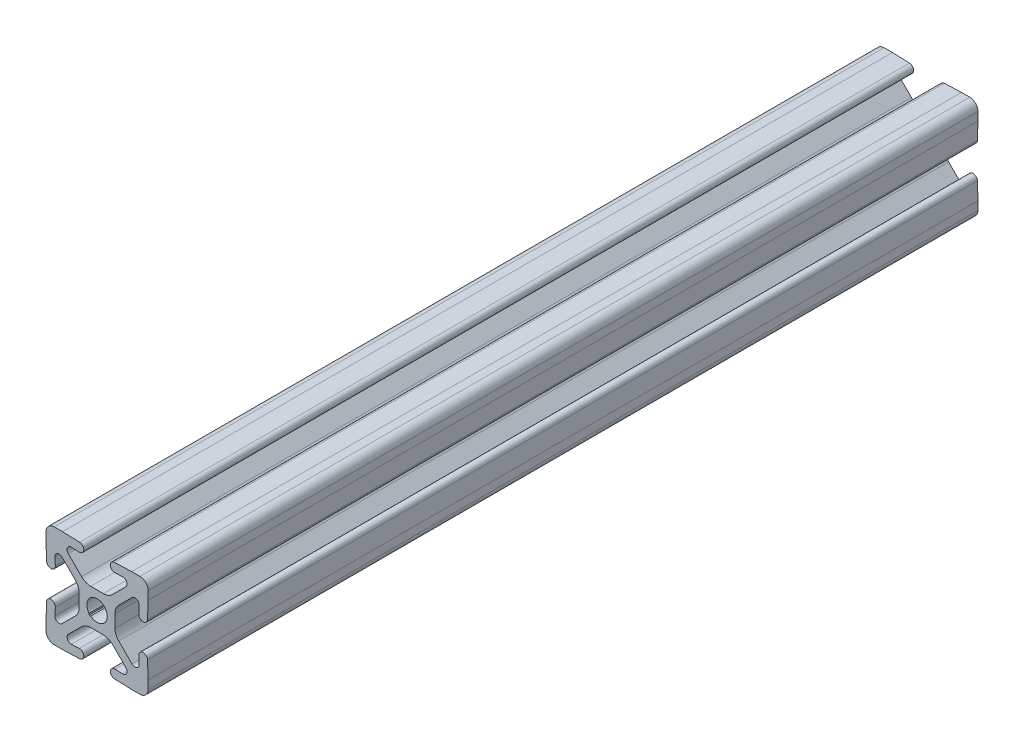
SolidWorks part; units mm, degrees
ref_plane "Front Plane" through (0, 0, 0) normal (0, 0, 1) x (1, 0, 0)
ref_plane "Top Plane" through (0, 0, 0) normal (0, 1, 0) x (1, 0, 0)
ref_plane "Right Plane" through (0, 0, 0) normal (1, 0, 0) x (0, 0, -1)
sketch "Model" plane through (0, 0, 0) normal (0, 0, 1) x (1, 0, 0)
  line L38 (50.6495, 75.4336) -> (50.2699, 75.4336)
  line L39 (50.2699, 75.4336) -> (50.2699, 75.8133)
  line L40 (50.66, 72.9999) -> (53.7746, 72.9999)
  line L41 (56.0196, 72.0699) -> (59.2642, 68.8254)
  line L42 (58.5103, 67.0916) -> (56.5725, 67.1592)
  line L43 (56.498, 65.0269) -> (60.6773, 64.881)
  line L44 (60.6773, 64.881) -> (62.7107, 64.881)
  line L45 (64.7173, 66.8876) -> (64.7173, 68.921)
  line L46 (64.7173, 68.921) -> (64.5713, 73.1002)
  line L47 (62.439, 73.0257) -> (62.5067, 71.0879)
  line L48 (60.7729, 70.334) -> (57.5283, 73.5786)
  line L49 (56.5984, 75.8237) -> (56.5984, 78.9383)
  line L50 (57.5283, 81.1833) -> (60.7729, 84.4279)
  line L51 (62.5067, 83.674) -> (62.439, 81.7362)
  line L52 (64.5713, 81.6617) -> (64.7173, 85.841)
  line L53 (64.7173, 85.841) -> (64.7173, 87.8744)
  line L54 (62.7107, 89.881) -> (60.6773, 89.881)
  line L55 (60.6773, 89.881) -> (56.498, 89.735)
  line L56 (56.5725, 87.6027) -> (58.5103, 87.6704)
  line L57 (59.2642, 85.9366) -> (56.0196, 82.692)
  line L58 (53.7746, 81.7621) -> (50.66, 81.7621)
  line L59 (48.4149, 82.692) -> (45.1703, 85.9366)
  line L60 (45.9242, 87.6704) -> (47.862, 87.6027)
  line L61 (47.9365, 89.735) -> (43.7573, 89.881)
  line L62 (43.7573, 89.881) -> (41.7239, 89.881)
  line L63 (39.7173, 87.8744) -> (39.7173, 85.841)
  line L64 (39.7173, 85.841) -> (39.8632, 81.6617)
  line L65 (41.9955, 81.7362) -> (41.9278, 83.674)
  line L66 (43.6616, 84.4279) -> (46.9062, 81.1833)
  line L67 (47.8361, 78.9383) -> (47.8361, 75.8237)
  line L68 (46.9062, 73.5786) -> (43.6616, 70.334)
  line L69 (41.9278, 71.0879) -> (41.9955, 73.0257)
  line L70 (39.8632, 73.1002) -> (39.7173, 68.921)
  line L71 (39.7173, 68.921) -> (39.7173, 66.8876)
  line L72 (41.7239, 64.881) -> (43.7573, 64.881)
  line L73 (43.7573, 64.881) -> (47.9365, 65.0269)
  line L74 (47.862, 67.1592) -> (45.9242, 67.0916)
  line L75 (45.1703, 68.8254) -> (48.4149, 72.0699)
  arc A29 (50.6495, 75.4336) -> (50.2699, 75.8133) centre (52.2173, 77.381) ccw
  arc A30 (56.0196, 72.0699) -> (53.7746, 72.9999) centre (53.7746, 69.8249) ccw
  arc A31 (58.5103, 67.0916) -> (59.2642, 68.8254) centre (58.5458, 68.1069) ccw
  arc A32 (56.5725, 67.1592) -> (56.498, 65.0269) centre (56.5353, 66.0931) ccw
  arc A33 (62.7107, 64.881) -> (64.7173, 66.8876) centre (62.7107, 66.8876) ccw
  arc A34 (64.5713, 73.1002) -> (62.439, 73.0257) centre (63.5052, 73.063) ccw
  arc A35 (60.7729, 70.334) -> (62.5067, 71.0879) centre (61.4913, 71.0525) ccw
  arc A36 (56.5984, 75.8237) -> (57.5283, 73.5786) centre (59.7734, 75.8237) ccw
  arc A37 (57.5283, 81.1833) -> (56.5984, 78.9383) centre (59.7734, 78.9383) ccw
  arc A38 (62.5067, 83.674) -> (60.7729, 84.4279) centre (61.4913, 83.7095) ccw
  arc A39 (62.439, 81.7362) -> (64.5713, 81.6617) centre (63.5052, 81.699) ccw
  arc A40 (64.7173, 87.8744) -> (62.7107, 89.881) centre (62.7107, 87.8744) ccw
  arc A41 (56.498, 89.735) -> (56.5725, 87.6027) centre (56.5353, 88.6689) ccw
  arc A42 (59.2642, 85.9366) -> (58.5103, 87.6704) centre (58.5458, 86.655) ccw
  arc A43 (53.7746, 81.7621) -> (56.0196, 82.692) centre (53.7746, 84.9371) ccw
  arc A44 (48.4149, 82.692) -> (50.66, 81.7621) centre (50.66, 84.9371) ccw
  arc A45 (45.9242, 87.6704) -> (45.1703, 85.9366) centre (45.8887, 86.655) ccw
  arc A46 (47.862, 87.6027) -> (47.9365, 89.735) centre (47.8993, 88.6689) ccw
  arc A47 (41.7239, 89.881) -> (39.7173, 87.8744) centre (41.7239, 87.8744) ccw
  arc A48 (39.8632, 81.6617) -> (41.9955, 81.7362) centre (40.9293, 81.699) ccw
  arc A49 (43.6616, 84.4279) -> (41.9278, 83.674) centre (42.9432, 83.7095) ccw
  arc A50 (47.8361, 78.9383) -> (46.9062, 81.1833) centre (44.6611, 78.9383) ccw
  arc A51 (46.9062, 73.5786) -> (47.8361, 75.8237) centre (44.6611, 75.8237) ccw
  arc A52 (41.9278, 71.0879) -> (43.6616, 70.334) centre (42.9432, 71.0525) ccw
  arc A53 (41.9955, 73.0257) -> (39.8632, 73.1002) centre (40.9293, 73.063) ccw
  arc A54 (39.7173, 66.8876) -> (41.7239, 64.881) centre (41.7239, 66.8876) ccw
  arc A55 (47.9365, 65.0269) -> (47.862, 67.1592) centre (47.8993, 66.0931) ccw
  arc A56 (45.1703, 68.8254) -> (45.9242, 67.0916) centre (45.8887, 68.1069) ccw
  arc A57 (50.66, 72.9999) -> (48.4149, 72.0699) centre (50.66, 69.8249) ccw
extrude "Boss-Extrude1" add sketch "Model" along normal blind 203.2
